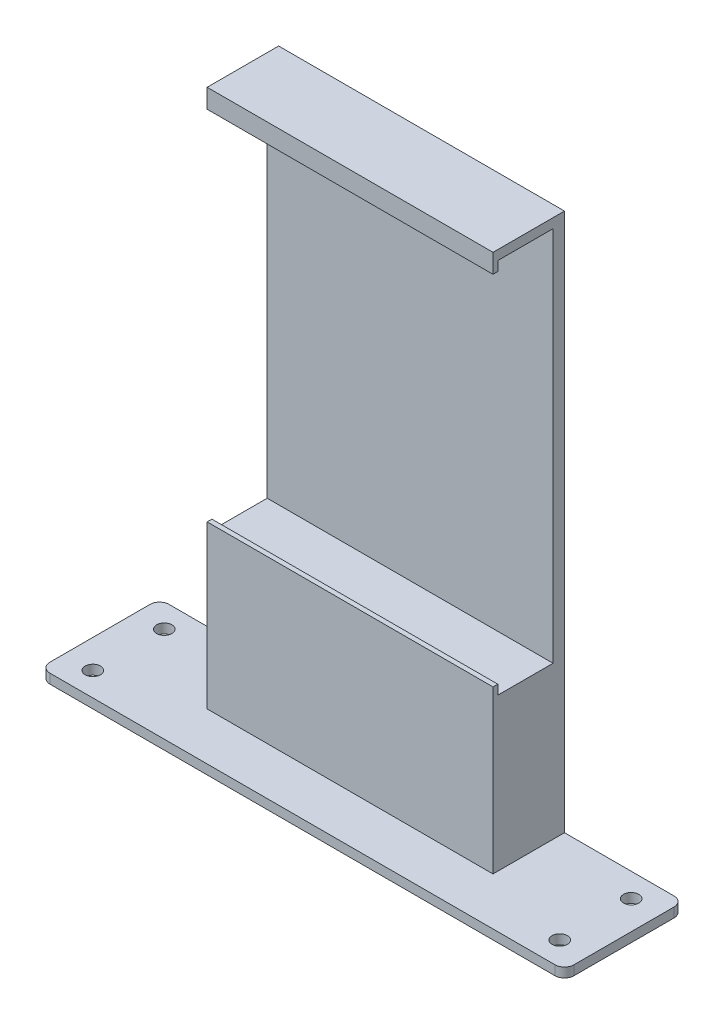
SolidWorks part; units mm, degrees
ref_plane "前视基准面" through (0, 0, 0) normal (0, 0, 1) x (1, 0, 0)
ref_plane "上视基准面" through (0, 0, 0) normal (0, 1, 0) x (1, 0, 0)
ref_plane "右视基准面" through (0, 0, 0) normal (1, 0, 0) x (0, 0, -1)
other "Configuration Table"
sketch "草图1" plane through (0, 0, 0) normal (0, 1, 0) x (1, 0, 0)
  line L0 (0, 0) -> (0, -50000) construction
  line L1 (-55, 12.5) -> (55, 12.5)
  line L2 (-55, 12.5) -> (-55, -12.5)
  line L3 (-55, -12.5) -> (55, -12.5)
  line L4 (55, 12.5) -> (55, -12.5)
  line L5 (-55, 12.5) -> (55, -12.5) construction
  line L6 (-55, -12.5) -> (55, 12.5) construction
  line L7 (0, 0) -> (-50000, 0) construction
  circle A0 centre (-49, 7.5) radius 1.6
  circle A1 centre (49, 7.5) radius 1.6
  circle A2 centre (49, -7.5) radius 1.6
  circle A3 centre (-49, -7.5) radius 1.6
  point P0 (0, 0)
  dimension "D3" = 3.2
  dimension "D1" = 110
  dimension "D2" = 25
  dimension "D4" = 15
  dimension "D5" = 98
extrude "凸台-拉伸1" add sketch "草图1" along normal blind 2
ref_plane "基准面1" through (0, 115, 0) normal (0, 1, 0) x (1, 0, 0)
sketch "草图2" plane through (0, 115, 0) normal (0, 1, 0) x (1, 0, 0)
  line L0 (55, 12.5) -> (-55, 12.5) construction
  line L1 (0, 0) -> (0, -50000) construction
  line L2 (-30, 12.5) -> (-30, -2.5)
  line L3 (-30, -2.5) -> (30, -2.5)
  line L4 (30, -2.5) -> (30, 12.5)
  line L5 (30, 12.5) -> (-30, 12.5)
  point P0 (-30, 12.5)
  point P6 (30, 12.5)
  dimension "D1" = 60
  dimension "D2" = 15
extrude "凸台-拉伸2" add sketch "草图2" against normal up to surface (113 mm away) up to face at (49, 2, 9.1)
sketch "草图3" plane through (30, 0, 0) normal (1, 0, 0) x (0, 0, -1)
  line L0 (-2.5, 2) -> (-2.5, 115) construction
  line L1 (-2.5, 36) -> (-1.5, 36)
  line L2 (-1.5, 34) -> (10.1, 34)
  line L3 (-1.5, 36) -> (-1.5, 34)
  line L4 (10.1, 34) -> (10.1, 113)
  line L5 (10.1, 113) -> (-1.5, 113)
  line L6 (-1.5, 113) -> (-1.5, 111)
  line L7 (-1.5, 111) -> (-2.5, 111)
  line L8 (-2.5, 36) -> (-2.5, 111)
  line L10 (-12.5, 0) -> (12.5, 0) construction
  line L11 (13.75, 115) -> (-13.75, 115) construction
  line L12 (12.5, 2) -> (12.5, 115) construction
  point P0 (-2.5, 36)
  point P1 (-2.5, 111)
  point P7 (-2.5, 115)
  point P16 (12.5, 115)
  dimension "D1" = 75
  dimension "D2" = 1
  dimension "D3" = 2
  dimension "D4" = 11.6
  dimension "D5" = 79
  dimension "D6" = 11.6
  dimension "D7" = 2
  dimension "D8" = 4
extrude "切除-拉伸1" cut sketch "草图3" against normal up to surface (60 mm away) up to face at (-30, 58.5, -5)
fillet "圆角1" radius 2 1 edges at (55, 1, 12.5)
fillet "圆角2" radius 2 1 edges at (55, 1, -12.5)
fillet "圆角3" radius 2 1 edges at (-55, 1, -12.5)
fillet "圆角4" radius 2 1 edges at (-55, 1, 12.5)
